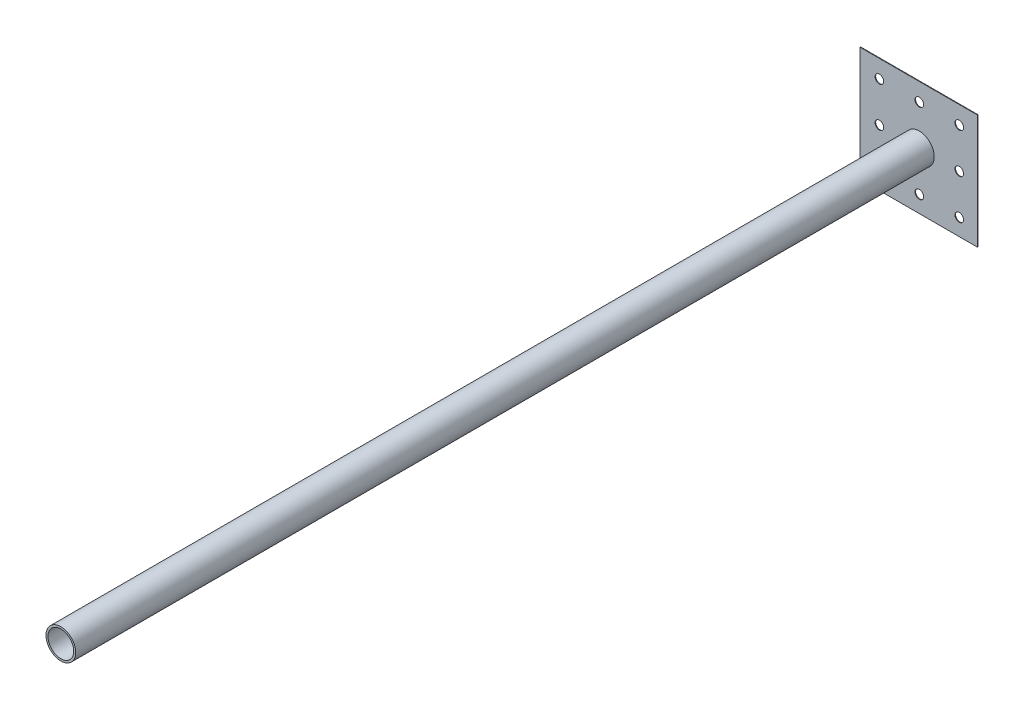
SolidWorks part; units mm, degrees
ref_plane "정면" through (0, 0, 0) normal (0, 0, 1) x (1, 0, 0)
ref_plane "윗면" through (0, 0, 0) normal (0, 1, 0) x (1, 0, 0)
ref_plane "우측면" through (0, 0, 0) normal (1, 0, 0) x (0, 0, -1)
sketch "스케치1" plane through (0, 0, 0) normal (0, 0, 1) x (1, 0, 0)
  line L4 (0, 40) -> (41, 40)
  line L5 (0, 40) -> (0, 0)
  line L6 (0, 0) -> (41, 0)
  line L7 (41, 40) -> (41, 0)
  dimension "D1" = 41
  dimension "D2" = 40
extrude "보스-돌출1" add sketch "스케치1" along normal blind 0.2
sketch "스케치5" plane through (0, 0, 0.2) normal (0, 0, 1) x (1, 0, 0)
  line L0 (41, 40) -> (0, 40) construction
  line L1 (41, 0) -> (41, 40) construction
  circle A0 centre (20.7, 19.8) radius 4.5
  dimension "D1" = 9
  dimension "D2" = 20.2
  dimension "D3" = 20.3
extrude "컷-돌출3" cut sketch "스케치5" against normal blind 0.2
sketch "스케치6" plane through (0, 0, 0.2) normal (0, 0, 1) x (1, 0, 0)
  line L1 (41, 0) -> (41, 40) construction
  line L3 (0, 40) -> (0, 0) construction
  line L4 (41, 40) -> (0, 40) construction
  circle A9 centre (20.7, 19.8) radius 4.5 construction
  circle A10 centre (20.7, 19.8) radius 4.5
  circle A11 centre (34.65, 19.8) radius 1.5
  circle A12 centre (20.7, 19.8) radius 4.5
  circle A13 centre (34.65, 5.85) radius 1.5
  circle A14 centre (20.7, 5.85) radius 1.5
  circle A15 centre (6.75, 19.8) radius 1.5
  circle A16 centre (20.7, 33.75) radius 1.5
  circle A17 centre (6.75, 5.85) radius 1.5
  circle A18 centre (6.75, 33.75) radius 1.5
  circle A19 centre (34.65, 33.75) radius 1.5
  point P0 (34.65, 5.85)
  point P9 (20.7, 19.8)
  point P13 (20.7, 19.8)
  point P17 (20.7, 19.8)
  point P28 (20.7, 19.8)
  dimension "D1" = 4
  dimension "D2" = 3
  dimension "D8" = 3
  dimension "D4" = 13.95
  dimension "D5" = 13.95
  dimension "D6" = 13.95
  dimension "D7" = 6.35
  dimension "D9" = 6.75
  dimension "D10" = 6.25
  dimension "D3" = 4
extrude "컷-돌출4" cut sketch "스케치6" against normal blind 0.2 contours A16 | A19 | A11 | A14 | A13 | A17 | A18 | A15
sketch "스케치7" plane through (0, 0, 0.2) normal (0, 0, 1) x (1, 0, 0)
  circle A0 centre (20.7, 19.8) radius 4.5
  circle A1 centre (20.7, 19.8) radius 5.2
  dimension "D1" = 0.7
  dimension "D2" = 9
extrude "보스-돌출2" add sketch "스케치7" along normal blind 300
